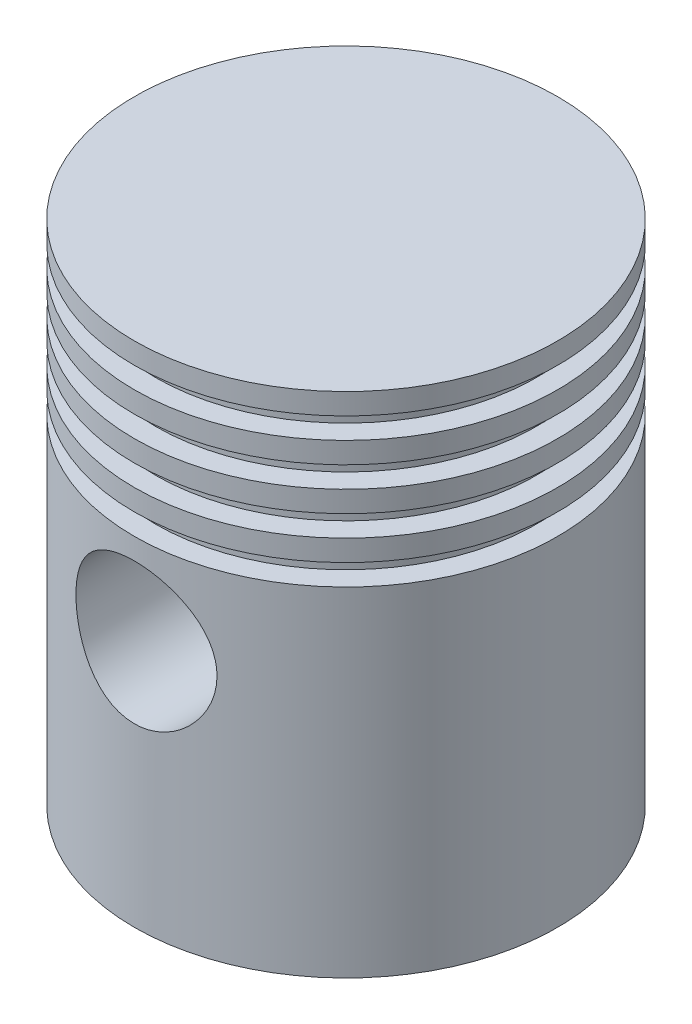
SolidWorks part; units mm, degrees
ref_plane "Front Plane" through (0, 0, 0) normal (0, 0, 1) x (1, 0, 0)
ref_plane "Top Plane" through (0, 0, 0) normal (0, 1, 0) x (1, 0, 0)
ref_plane "Right Plane" through (0, 0, 0) normal (1, 0, 0) x (0, 0, -1)
sketch "Sketch1" plane through (0, 0, 0) normal (1, 0, 0) x (0, 0, -1)
  line L0 (30, 37) -> (0, 37)
  line L1 (0, 37) -> (0, 25)
  line L2 (0, 25) -> (22, 25)
  line L4 (24, 23) -> (24, 15)
  line L9 (30, 13) -> (27, 13)
  line L10 (27, 13) -> (27, 16)
  line L11 (27, 16) -> (30, 16)
  line L12 (30, 16) -> (30, 19)
  line L13 (30, 19) -> (27, 19)
  line L14 (27, 19) -> (27, 22)
  line L15 (27, 22) -> (30, 22)
  line L16 (30, 22) -> (30, 25)
  line L17 (30, 25) -> (27, 25)
  line L18 (27, 25) -> (27, 28)
  line L19 (27, 28) -> (30, 28)
  line L20 (30, 28) -> (30, 31)
  line L21 (30, 31) -> (27, 31)
  line L22 (27, 31) -> (27, 34)
  line L23 (27, 34) -> (30, 34)
  line L24 (30, 34) -> (30, 37)
  line L26 (30, -35) -> (0, -35)
  line L27 (0, -35) -> (0, -32)
  line L28 (0, -32) -> (27, -32)
  line L34 (30, 13) -> (30, -35)
  line L36 (0, 50) -> (0, -50) construction
  line L39 (27, -32) -> (27, -13)
  line L40 (27, -13) -> (10, -13)
  line L41 (10, -13) -> (10, 13)
  line L42 (10, 13) -> (22, 13)
  arc A0 (24, 23) -> (22, 25) centre (22, 23) ccw
  arc A1 (22, 13) -> (24, 15) centre (22, 15) ccw
  point P3 (24, 19)
  point P30 (0, 0)
  point P37 (10, 0)
  point P38 (0, 27.6735)
  point P39 (30, -34.5185)
  point P40 (26.2258, -13)
  dimension "D8" = 3
  dimension "D9" = 24
  dimension "D6" = 2
  dimension "D7" = 2
  dimension "D1" = 3
  dimension "D2" = 10
  dimension "D3" = 12
  dimension "D4" = 26
  dimension "D5" = 30
  dimension "D10" = 3
  dimension "D11" = 35
  dimension "D12" = 100
  dimension "D13" = 3
revolve "Revolve4" add sketch "Sketch1" angle 360 about L36
sketch "Sketch7" plane through (0, 0, 0) normal (0, 0, 1) x (1, 0, 0)
  circle A0 centre (0, 0) radius 10
  dimension "D1" = 20
extrude "Cut-Extrude7" cut sketch "Sketch7" against normal through all and the other way through all
chamfer "Chamfer6" distance 0.25 angle 45 1 edges at (0, -32, 27)
chamfer "Chamfer7" distance 0.25 angle 45 1 edges at (0, -13, 27)
